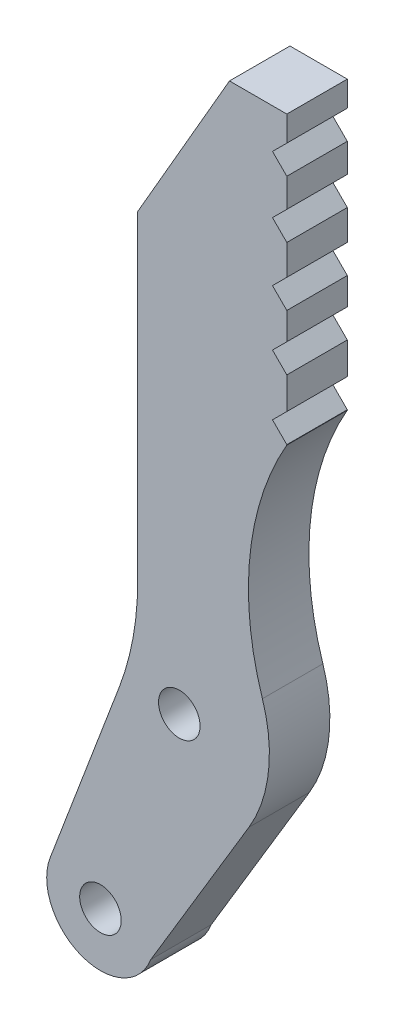
SolidWorks part; units mm, degrees
ref_plane "Front Plane" through (0, 0, 0) normal (0, 0, 1) x (1, 0, 0)
ref_plane "Top Plane" through (0, 0, 0) normal (0, 1, 0) x (1, 0, 0)
ref_plane "Right Plane" through (0, 0, 0) normal (1, 0, 0) x (0, 0, -1)
sketch "Sketch1" plane through (0, 0, 0) normal (0, 0, 1) x (1, 0, 0)
  line L0 (6.985, 18.415) -> (0, 0) construction
  line L3 (20.9869, 18.415) -> (16.51, 18.415) construction
  line L10 (4.1556, 18.415) -> (-12.6376, 18.415) construction
  line L12 (20.9869, 18.415) -> (16.51, 18.415) construction
  line L15 (0, 0) -> (6.985, 18.415) construction
  line L19 (-1.2084, 47.3246) -> (-1.2084, 10.2427)
  line L21 (0, 0) -> (6.985, 18.415) construction
  line L30 (16.51, 69.215) -> (16.51, 43.815)
  line L31 (0, 0) -> (6.985, 18.415) construction
  line L36 (11.43, 18.415) -> (-26.9598, 18.415) construction
  line L38 (15.0503, 0.635) -> (5.4573, 0.635) construction
  line L40 (0, 0) -> (6.985, 18.415) construction
  line L43 (5.1904, 0.635) -> (-19.2665, 0.635) construction
  line L44 (0, 0) -> (6.985, 18.415) construction
  line L45 (-4.4529, 1.689) -> (-1.2084, 10.2427)
  line L47 (4.4529, -1.689) -> (16.51, 18.415)
  line L48 (16.51, 69.215) -> (11.43, 69.215)
  line L49 (11.43, 69.215) -> (-1.2084, 47.3246)
  circle A8 centre (0, 0) radius 1.8415
  circle A9 centre (6.985, 18.415) radius 1.8415
  arc A27 (-4.4529, 1.689) -> (4.4529, -1.689) centre (0, 0) ccw
  arc A28 (16.51, 43.815) -> (16.51, 18.415) centre (38.507, 31.115) ccw
  point P0 (11.2903, 20.32)
  point P3 (5.08, 13.97)
  point P6 (4.9403, 14.2021)
  point P7 (5.08, 13.97)
  point P17 (3.4925, 12.3825)
  point P21 (5.8737, 13.97)
  point P22 (3.4925, 12.3825)
  point P23 (3.4925, 9.2075)
  dimension "D3" = 6.985
  dimension "D4" = 50.8
  dimension "D5" = 18.415
  dimension "D1" = 3.683
  dimension "D2" = 3.683
  dimension "D10" = 25.4
  dimension "D8" = 4.7625
  dimension "D9" = 25.4
  dimension "D12" = 5.08
extrude "Boss-Extrude1" add sketch "Sketch1" along normal blind 5.08 and the other way blind 0.2784
sketch "Sketch2" plane through (0, 0, -0.2784) normal (0, 0, -1) x (-1, 0, 0)
  line L0 (-16.51, 56.6859) -> (-15.24, 55.4159)
  line L1 (-16.51, 72.5832) -> (-15.24, 72.5832)
  line L2 (-16.51, 72.5832) -> (-16.51, 43.8497)
  line L4 (-15.24, 72.5832) -> (-15.24, 45.1197)
  line L5 (-15.24, 55.4159) -> (-16.51, 54.1459)
  line L6 (-16.51, 51.7421) -> (-15.24, 50.4721)
  line L7 (-16.51, 43.815) -> (-16.51, 69.215) construction
  line L8 (-15.24, 50.4721) -> (-16.51, 49.2021)
  line L13 (-15.24, 45.1197) -> (-16.51, 43.8497)
  line L14 (-16.51, 66.9821) -> (-15.24, 65.7121)
  line L15 (-15.24, 65.7121) -> (-16.51, 64.4421)
  line L16 (-16.51, 61.9021) -> (-15.24, 60.6321)
  line L17 (-15.24, 60.6321) -> (-16.51, 59.3621)
  line L18 (-16.51, 46.3897) -> (-15.24, 45.1197)
  dimension "D1" = 1.27
extrude "Cut-Extrude1" cut sketch "Sketch2" against normal through all both and the other way through all
sketch "Sketch5" plane through (0, 0, -0.2784) normal (0, 0, -1) x (-1, 0, 0)
  line L0 (-11.43, 88.265) -> (-11.43, -1.8809) construction
  line L1 (-16.51, 66.9821) -> (-16.51, 69.215) construction
  text T0 "<b>KAPTA</b>" font "Verdana" height 5.08
  dimension "D1" = 5.08
extrude "Boss-Extrude2" add sketch "Sketch5" along normal blind 0.635
fillet "Fillet2" radius 12.7 2 edges at (-1.2084, 10.2427, 2.4008) (16.51, 18.415, 2.4008)
sketch "Sketch6" plane through (0, 0, -0.2784) normal (0, 0, -1) x (-1, 0, 0)
  line L1 (-3.302, 55.1369) -> (1.8566, 55.1369)
  line L2 (-3.302, 55.1369) -> (-3.302, 22.1338)
  line L4 (1.8566, 55.1369) -> (1.8566, 24.765)
  line L8 (12.8138, 19.4727) -> (1.8566, 24.765)
  line L9 (-16.51, 66.9821) -> (-16.51, 69.215) construction
  line L10 (4.4529, 1.689) -> (-2.5321, 20.104)
  line L11 (12.8138, 19.4727) -> (4.4529, 1.689)
  line L12 (-2.5321, 20.104) -> (-3.302, 22.1338)
  line L13 (-11.43, 69.215) -> (1.2084, 47.3246) construction
  point P4 (0, 0)
  dimension "D1" = 13.208
extrude "Cut-Extrude2" cut sketch "Sketch6" against normal through all both and the other way through all
fillet "Fillet3" radius 25.4 1 edges at (3.302, 22.1338, 2.4008)
